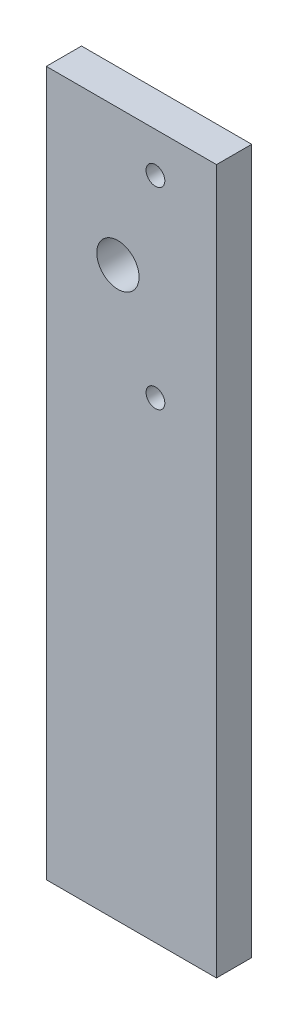
SolidWorks part; units mm, degrees
ref_plane "Alzado" through (0, 0, 0) normal (0, 0, 1) x (1, 0, 0)
ref_plane "Planta" through (0, 0, 0) normal (0, 1, 0) x (1, 0, 0)
ref_plane "Vista lateral" through (0, 0, 0) normal (1, 0, 0) x (0, 0, -1)
sketch "Croquis1" plane through (0, 0, 0) normal (0, 0, 1) x (1, 0, 0)
  line L1 (0, 0) -> (72.48, 0)
  line L2 (0, 0) -> (0, 300)
  line L3 (0, 300) -> (72.48, 300)
  line L4 (72.48, 0) -> (72.48, 300)
  circle A0 centre (46.48, 283) radius 4
  circle A1 centre (46.48, 201) radius 4
  circle A2 centre (30.5, 242) radius 9
  dimension "D3" = 8
  dimension "D7" = 18
  dimension "D1" = 300
  dimension "D2" = 72.48
  dimension "D4" = 82
  dimension "D5" = 17
  dimension "D6" = 26
  dimension "D8" = 30.5
  dimension "D9" = 58
extrude "Saliente-Extruir1" add sketch "Croquis1" along normal blind 15
